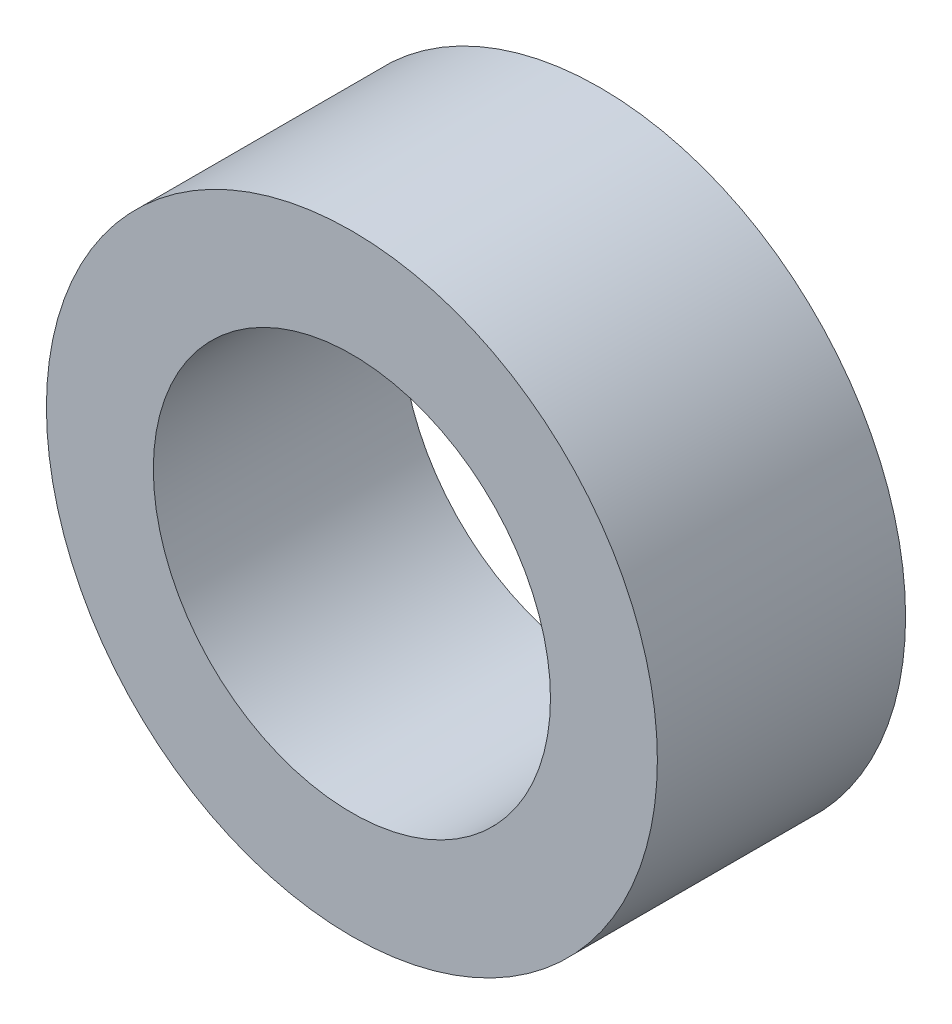
SolidWorks part; units mm, degrees
ref_plane "前视基准面" through (0, 0, 0) normal (0, 0, 1) x (1, 0, 0)
ref_plane "上视基准面" through (0, 0, 0) normal (0, 1, 0) x (1, 0, 0)
ref_plane "右视基准面" through (0, 0, 0) normal (1, 0, 0) x (0, 0, -1)
sketch "草图1" plane through (0, 0, 0) normal (0, 0, 1) x (1, 0, 0)
  circle A0 centre (0, 0) radius 2.6
  circle A1 centre (0, 0) radius 4
  dimension "D1" = 5.2
  dimension "D2" = 8
extrude "凸台-拉伸1" add sketch "草图1" along normal blind 3.25
